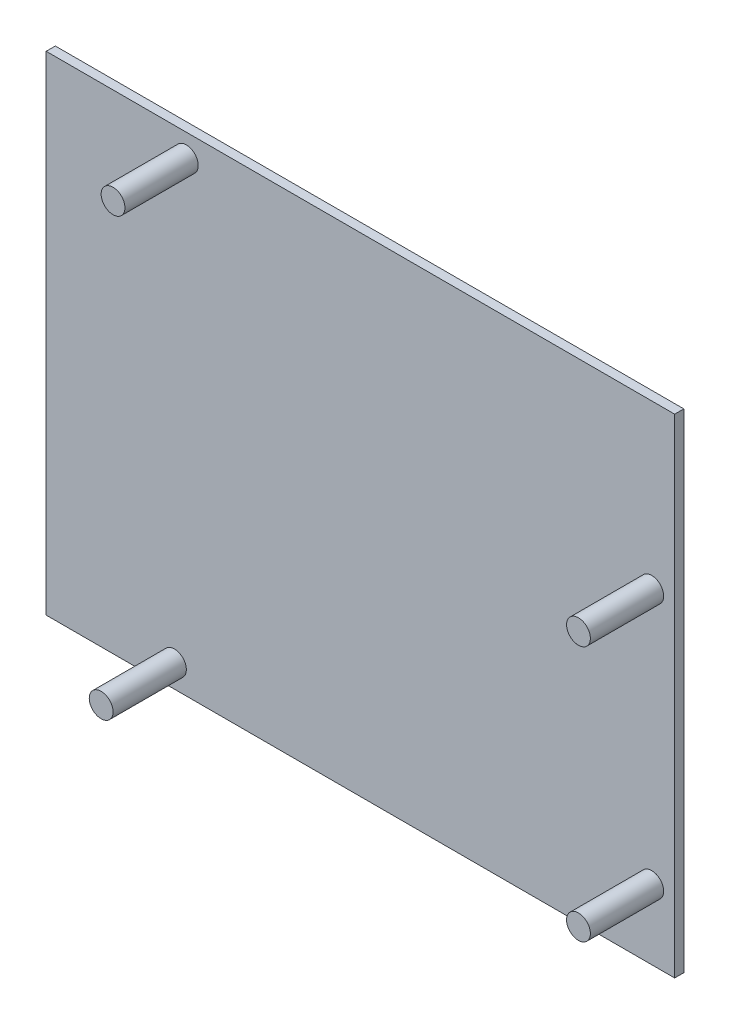
SolidWorks part; units mm, degrees
ref_plane "Front Plane" through (0, 0, 0) normal (0, 0, 1) x (1, 0, 0)
ref_plane "Top Plane" through (0, 0, 0) normal (0, 1, 0) x (1, 0, 0)
ref_plane "Right Plane" through (0, 0, 0) normal (1, 0, 0) x (0, 0, -1)
sketch "Sketch1" plane through (0, 0, 0) normal (0, 0, 1) x (1, 0, 0)
  line L1 (0, 0) -> (68.6, 0)
  line L2 (0, 0) -> (0, 53.3)
  line L3 (0, 53.3) -> (68.6, 53.3)
  line L4 (68.6, 0) -> (68.6, 53.3)
  dimension "D1" = 68.6
  dimension "D2" = 53.3
extrude "Boss-Extrude1" add sketch "Sketch1" along normal blind 1
sketch "Sketch2" plane through (0, 0, 1) normal (0, 0, 1) x (1, 0, 0)
  circle A0 centre (14, 2.5) radius 1.3
  circle A1 centre (15.3, 50.8) radius 1.3
  circle A2 centre (66.1, 7.6) radius 1.3
  circle A3 centre (66.1, 35.5) radius 1.3
extrude "Boss-Extrude2" add sketch "Sketch2" along normal blind 8
